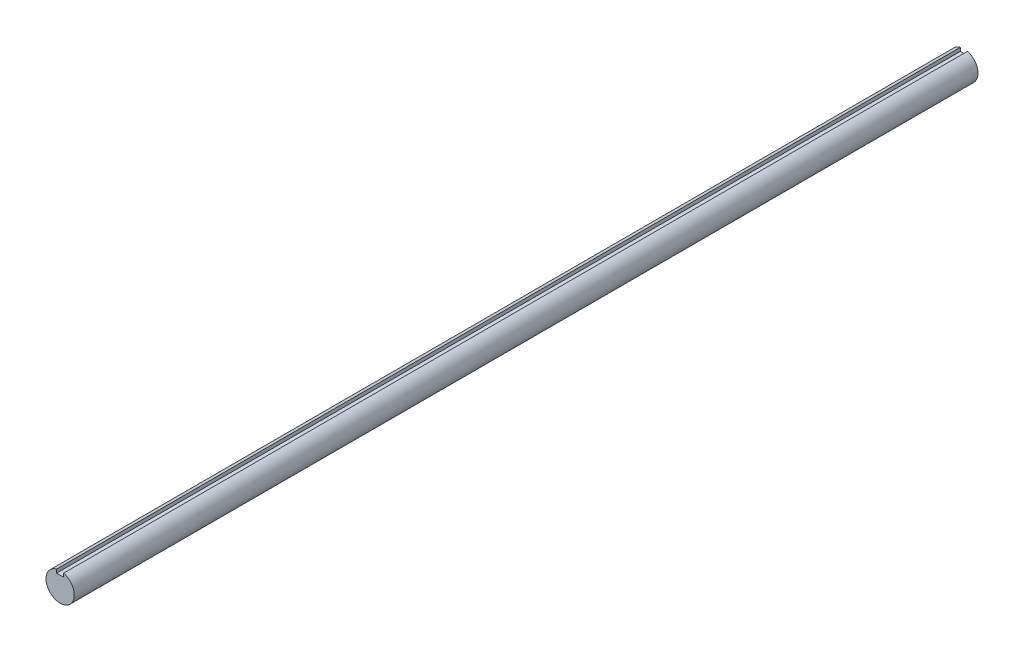
SolidWorks part; units mm, degrees
ref_plane "Front Plane" through (0, 0, 0) normal (0, 0, 1) x (1, 0, 0)
ref_plane "Top Plane" through (0, 0, 0) normal (0, 1, 0) x (1, 0, 0)
ref_plane "Right Plane" through (0, 0, 0) normal (1, 0, 0) x (0, 0, -1)
sketch "Sketch1" plane through (0, 0, 0) normal (1, 0, 0) x (0, 0, -1)
  line L0 (0, 0) -> (0, 9.525) construction
  line L1 (-304.8, 9.525) -> (304.8, 9.525)
  line L2 (-304.8, 9.525) -> (-304.8, -9.525)
  line L3 (-304.8, -9.525) -> (304.8, -9.525)
  line L4 (304.8, 9.525) -> (304.8, -9.525)
  line L5 (-304.8, 9.525) -> (304.8, -9.525) construction
  line L6 (-304.8, -9.525) -> (304.8, 9.525) construction
  line L7 (0, 0) -> (0, -9.525) construction
  point P0 (0, 0)
  point P8 (-282.8925, 9.525)
  point P10 (282.8925, 9.525)
  point P11 (-275.59, -9.525)
  point P12 (279.5035, -9.525)
  dimension "Diameter" = 19.05
  dimension "Length" = 609.6
  dimension "D1" = 21.9075
  dimension "D2" = 21.9075
  dimension "D3" = 29.21
  dimension "D4" = 25.2965
sketch "Sketch2" plane through (0, 0, 0) normal (0, 0, 1) x (1, 0, 0)
  line L0 (0, 0) -> (0, 9.525) construction
  line L2 (2.3876, 6.8333) -> (-2.3876, 6.8333)
  line L3 (2.3876, 6.8333) -> (2.3876, 9.2209)
  line L4 (2.3876, 9.2209) -> (-2.3876, 9.2209)
  line L5 (-2.3876, 6.8333) -> (-2.3876, 9.2209)
  line L6 (2.3876, 6.8333) -> (-2.3876, 9.2209) construction
  line L7 (2.3876, 9.2209) -> (-2.3876, 6.8333) construction
  circle A0 centre (0, 0) radius 9.525
  point P3 (0, 8.0271)
  dimension "Keyway Width" = 4.7752
  dimension "Keyway Depth" = 2.3876
sketch "Sketch3" plane through (0, 0, 0) normal (0, 0, 1) x (1, 0, 0)
  line L1 (-2.3876, 6.8333) -> (-2.3876, 9.2209) construction
  line L2 (2.3876, 6.8333) -> (-2.3876, 6.8333) construction
  line L3 (2.3876, 6.8333) -> (2.3876, 9.2209) construction
  line L5 (-2.3876, 6.8333) -> (-2.3876, 9.2209)
  line L6 (2.3876, 6.8333) -> (-2.3876, 6.8333)
  line L7 (2.3876, 6.8333) -> (2.3876, 9.2209)
  circle A0 centre (0, 0) radius 9.525 construction
  arc A1 (-2.3876, 9.2209) -> (2.3876, 9.2209) centre (0, 0) ccw
extrude "Boss-Extrude1" add sketch "Sketch3" along normal up to vertex (304.8 mm away) and the other way up to vertex (304.8 mm away) up to point (0, 9.525, 304.8) other way up to point (0, 9.525, -304.8)
equation "\"D2@Sketch1\"=1.15*\"Diameter@Sketch1\""
equation "\"D1@Sketch1\"=\"D2@Sketch1\""
equation "\"D3@Sketch1\"=\"D2@Sketch1\"*4/3"
equation "\"D4@Sketch1\"=\"D2@Sketch1\"/(tan(.5236*180/pi)*2)*4/3"
